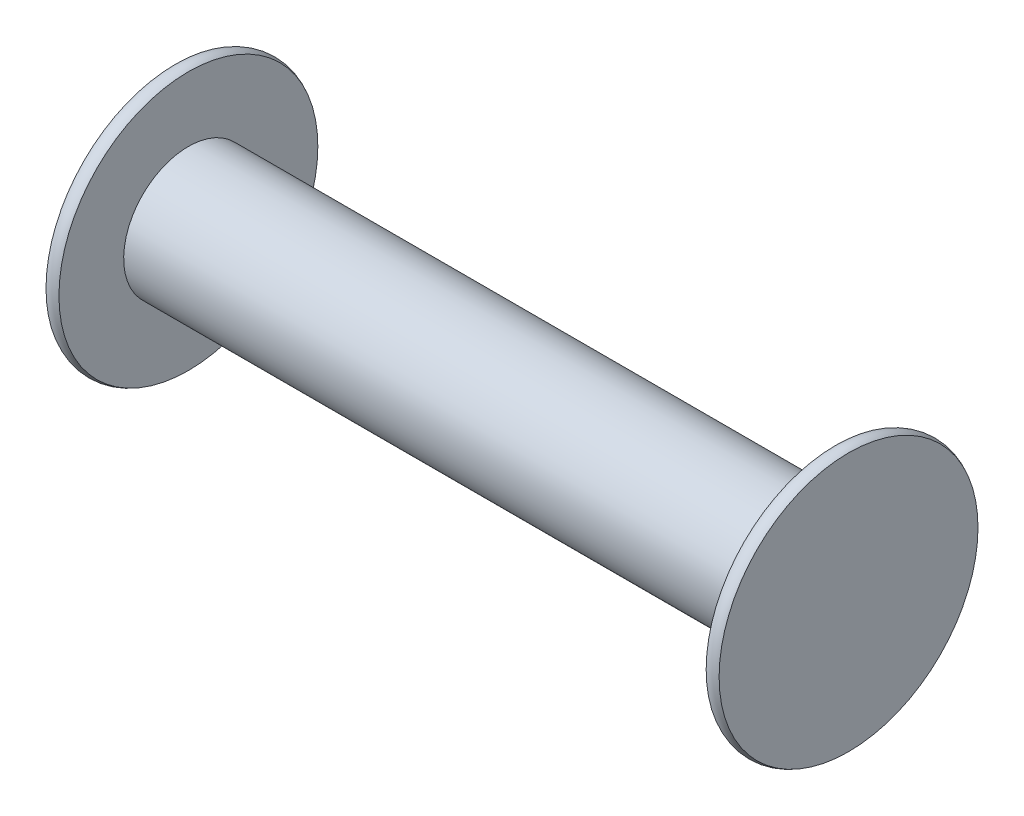
SolidWorks part; units mm, degrees
ref_plane "Ön Düzlem" through (0, 0, 0) normal (0, 0, 1) x (1, 0, 0)
ref_plane "Üst Düzlem" through (0, 0, 0) normal (0, 1, 0) x (1, 0, 0)
ref_plane "Sağ Düzlem" through (0, 0, 0) normal (1, 0, 0) x (0, 0, -1)
sketch "Sketch1" plane through (0, 0, 0) normal (0, 0, 1) x (1, 0, 0)
  line L0 (-26, 0) -> (26, 0)
  line L1 (-26, 0) -> (-26, -10)
  line L2 (-21, -5) -> (12.75, -5) construction
  line L3 (-25, -5) -> (25, -5)
  line L4 (-21, -5) -> (-21, -10) construction
  line L5 (-25, -1) -> (-25, -10) construction
  line L6 (-25, -5) -> (-25, -10)
  line L7 (-25, -1) -> (12.75, -1) construction
  line L8 (0, 0) -> (0, -5.3304) construction
  line L9 (-26, 0) -> (12.75, 0) construction
  line L10 (25, -5) -> (25, -10)
  line L11 (26, 0) -> (26, -10)
  arc A0 (-26, -10) -> (-25, -10) centre (-25.5, -9.134) ccw
  arc A1 (26, -10) -> (25, -10) centre (25.5, -9.134) cw
  point P20 (0, -5)
  dimension "D5" = 1
  dimension "D1" = 26
  dimension "D2" = 10
  dimension "D3" = 5
  dimension "D4" = 1
revolve "Revolve1" add sketch "Sketch1" angle 360 about L0
